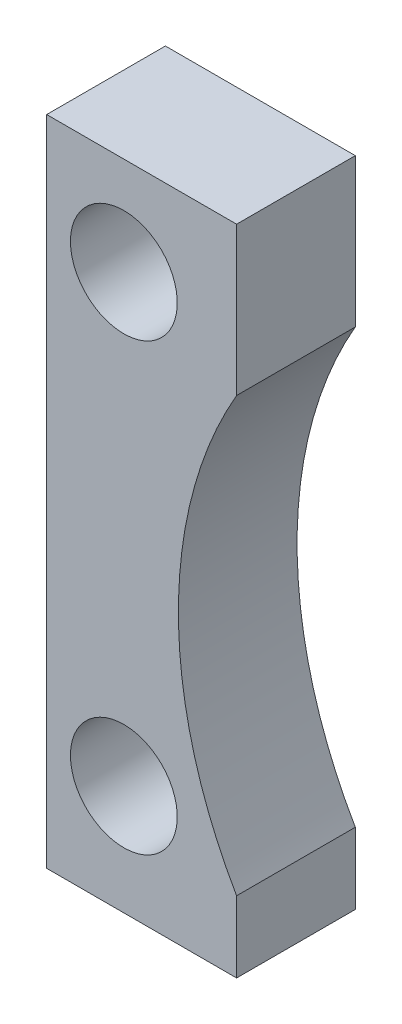
SolidWorks part; units mm, degrees
ref_plane "Ön Düzlem" through (0, 0, 0) normal (0, 0, 1) x (1, 0, 0)
ref_plane "Üst Düzlem" through (0, 0, 0) normal (0, 1, 0) x (1, 0, 0)
ref_plane "Sağ Düzlem" through (0, 0, 0) normal (1, 0, 0) x (0, 0, -1)
sketch "Çizim1" plane through (0, 0, 0) normal (0, 0, 1) x (1, 0, 0)
  line L0 (0, 110) -> (32, 110)
  line L1 (0, 110) -> (0, 0)
  line L2 (0, 0) -> (32, 0)
  line L3 (32, 110) -> (32, 85)
  line L4 (32, 12) -> (32, 0)
  arc A0 (32, 85) -> (32, 12) centre (95, 48.5) ccw
  dimension "D1" = 110
  dimension "D2" = 32
  dimension "D3" = 25
  dimension "D4" = 12
  dimension "D5" = 95
extrude "Yükseklik-Ekstrüzyon1" add sketch "Çizim1" along normal mid plane 20
sketch "Çizim2" plane through (0, 0, -10) normal (0, 0, -1) x (-1, 0, 0)
  line L0 (0, 110) -> (0, 0) construction
  line L1 (-32, 110) -> (0, 110) construction
  circle A0 centre (-13, 93.5) radius 9
  circle A1 centre (-13, 18.5) radius 9
  point P10 (0, 0)
  dimension "D3" = 18
  dimension "D1" = 75
  dimension "D2" = 13
  dimension "D4" = 16.5
extrude "Kes-Ekstrüzyon1" cut sketch "Çizim2" against normal through all
